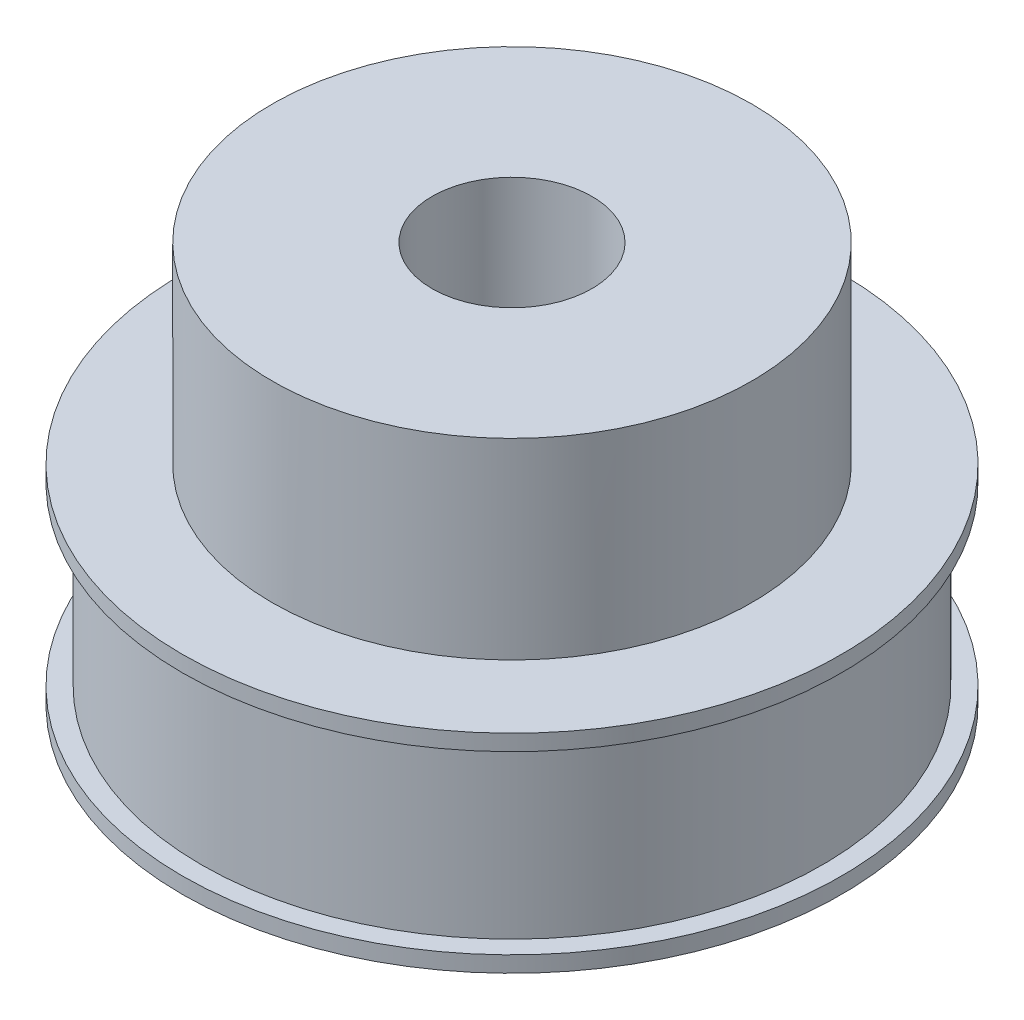
SolidWorks part; units mm, degrees
ref_plane "前视基准面" through (0, 0, 0) normal (0, 0, 1) x (1, 0, 0)
ref_plane "上视基准面" through (0, 0, 0) normal (0, 1, 0) x (1, 0, 0)
ref_plane "右视基准面" through (0, 0, 0) normal (1, 0, 0) x (0, 0, -1)
sketch "草图1" plane through (0, 0, 0) normal (0, 1, 0) x (1, 0, 0)
  circle A0 centre (0, 0) radius 19.405
  dimension "D1" = 38.81
extrude "凸台-拉伸1" add sketch "草图1" along normal blind 11
ref_plane "基准面1" through (0, 5.5, 0) normal (0, 1, 0) x (1, 0, 0)
sketch "草图2" plane through (0, 11, 0) normal (0, 1, 0) x (1, 0, 0)
  circle A0 centre (0, 0) radius 20.605
  circle A1 centre (0, 0) radius 19.405
  circle A2 centre (0, 0) radius 19.405 construction
  dimension "D2" = 1.2
  dimension "D1" = 0
extrude "凸台-拉伸2" add sketch "草图2" along normal blind 1
mirror "镜向1" about plane through (0, 5.5, 0) normal (0, 1, 0) of "凸台-拉伸2"
sketch "草图3" plane through (0, 12, 0) normal (0, 1, 0) x (1, 0, 0)
  circle A0 centre (0, 0) radius 15
  dimension "D1" = 30
extrude "凸台-拉伸3" add sketch "草图3" along normal offset from surface (12 mm away) 25 up to face at (0, -1, 20.605)
sketch "草图4" plane through (0, 24, 0) normal (0, 1, 0) x (1, 0, 0)
  circle A0 centre (0, 0) radius 5
  dimension "D1" = 10
extrude "切除-拉伸1" cut sketch "草图4" against normal through all
